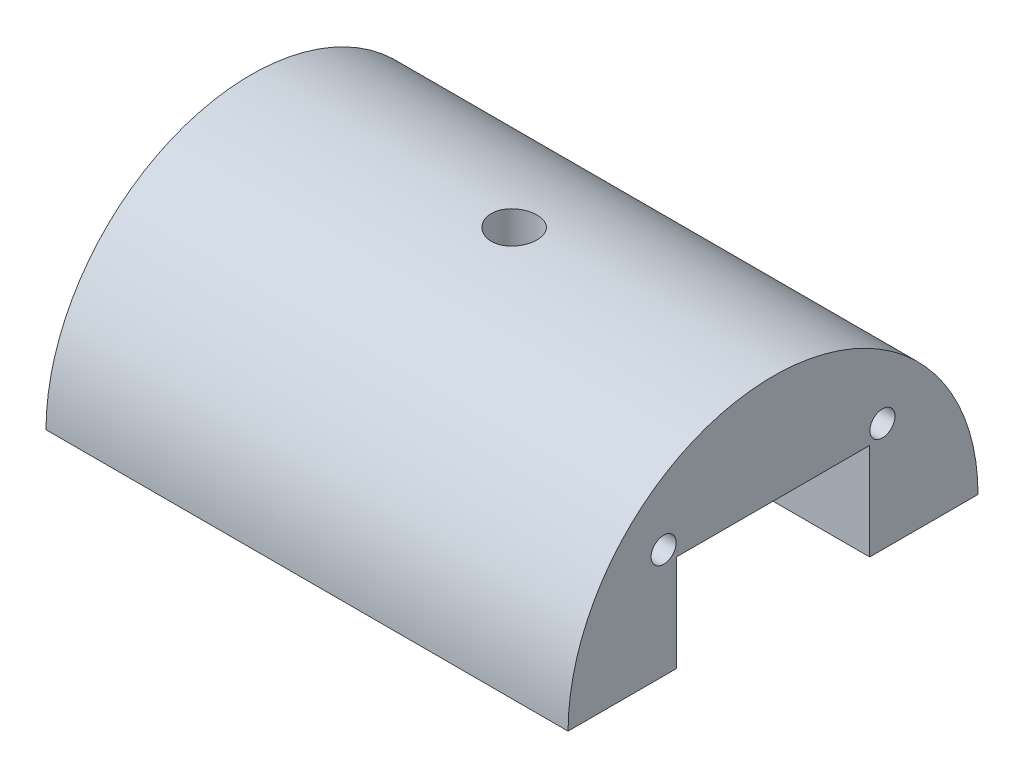
SolidWorks part; units mm, degrees
ref_plane "Front Plane" through (0, 0, 0) normal (0, 0, 1) x (1, 0, 0)
ref_plane "Top Plane" through (0, 0, 0) normal (0, 1, 0) x (1, 0, 0)
ref_plane "Right Plane" through (0, 0, 0) normal (1, 0, 0) x (0, 0, -1)
sketch "Sketch2" plane through (0, 0, 0) normal (1, 0, 0) x (0, 0, -1)
  line L0 (-26.924, 0) -> (-12.7, 0)
  line L1 (0, 0) -> (-14.3684, 14.3684) construction
  line L2 (-12.7, 12.7) -> (12.7, 12.7)
  line L3 (-12.7, 12.7) -> (-12.7, 0)
  line L5 (12.7, 12.7) -> (12.7, 0)
  line L6 (-12.7, 12.7) -> (0, 0) construction
  line L7 (0, 0) -> (12.7, 12.7) construction
  line L8 (0, 55) -> (0, -55) construction
  line L9 (12.7, 0) -> (26.924, 0)
  arc A0 (26.924, 0) -> (-26.924, 0) centre (0, 0) ccw
  circle A1 centre (-14.3684, 14.3684) radius 1.651
  circle A2 centre (14.3684, 14.3684) radius 1.651
  point P1 (-13.4704, 13.4704)
  point P5 (-13.4704, 13.4704)
  dimension "D1" = 53.848
  dimension "D3" = 3.302
  dimension "D2" = 25.4
  dimension "D4" = 20.32
  dimension "D5" = 45
  dimension "D6" = 12.7
extrude "Boss-Extrude1" add sketch "Sketch2" along normal blind 68.58 contours L2 A2 L5 L9 A0 L0 L3 A1
sketch "Sketch3" plane through (0, 0, 0) normal (0, 1, 0) x (1, 0, 0)
  circle A0 centre (34.5739, 0) radius 3
  dimension "D1" = 6
extrude "Cut-Extrude3" cut sketch "Sketch3" along normal through all both and the other way through all
